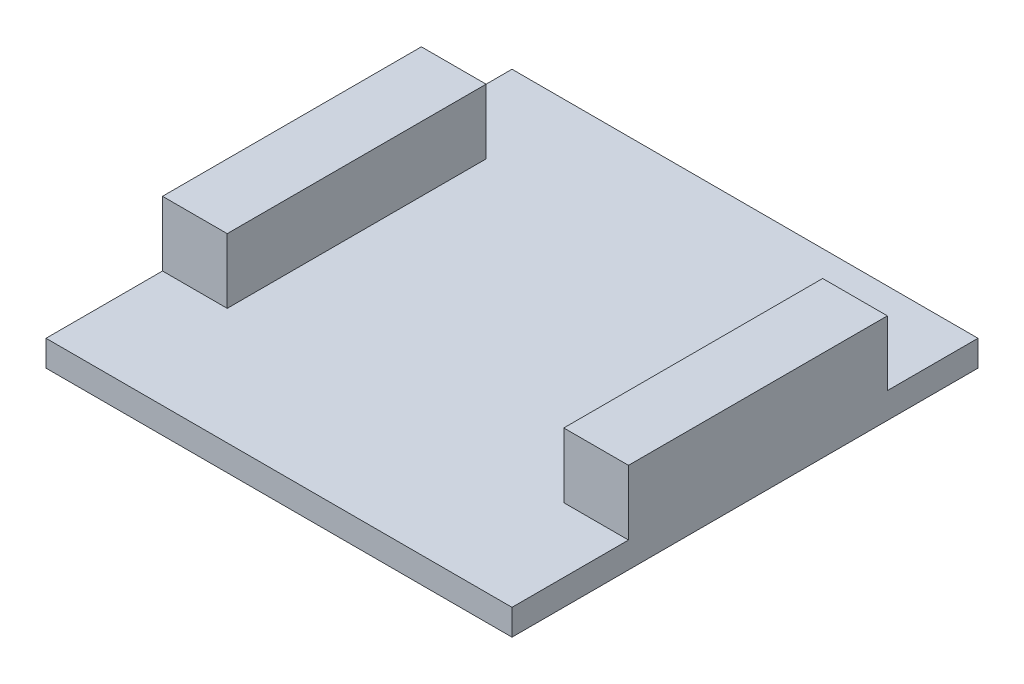
SolidWorks part; units mm, degrees
ref_plane "Front Plane" through (0, 0, 0) normal (0, 0, 1) x (1, 0, 0)
ref_plane "Top Plane" through (0, 0, 0) normal (0, 1, 0) x (1, 0, 0)
ref_plane "Right Plane" through (0, 0, 0) normal (1, 0, 0) x (0, 0, -1)
sketch "Sketch1" plane through (0, 0, 0) normal (0, 1, 0) x (1, 0, 0)
  line L1 (0, 0) -> (18, 0)
  line L2 (0, 0) -> (0, 18)
  line L3 (0, 18) -> (18, 18)
  line L4 (18, 0) -> (18, 18)
  dimension "D1" = 18
  dimension "D2" = 18
extrude "Boss-Extrude1" add sketch "Sketch1" along normal blind 1
sketch "Sketch2" plane through (0, 1, 0) normal (0, 1, 0) x (1, 0, 0)
  line L0 (9, 18) -> (9, 0) construction
  line L1 (18, 18) -> (0, 18) construction
  line L2 (0, 0) -> (18, 0) construction
  line L3 (0, 18) -> (0, 0) construction
  line L4 (0, 14.5) -> (2.5, 14.5)
  line L5 (0, 14.5) -> (0, 4.5)
  line L6 (0, 4.5) -> (2.5, 4.5)
  line L7 (2.5, 14.5) -> (2.5, 4.5)
  line L8 (15.5, 14.5) -> (15.5, 4.5)
  line L9 (18, 4.5) -> (15.5, 4.5)
  line L10 (18, 14.5) -> (18, 4.5)
  line L11 (18, 14.5) -> (15.5, 14.5)
  dimension "D1" = 10
  dimension "D2" = 2.5
  dimension "D3" = 3.5
extrude "Boss-Extrude2" add sketch "Sketch2" along normal blind 2.5
